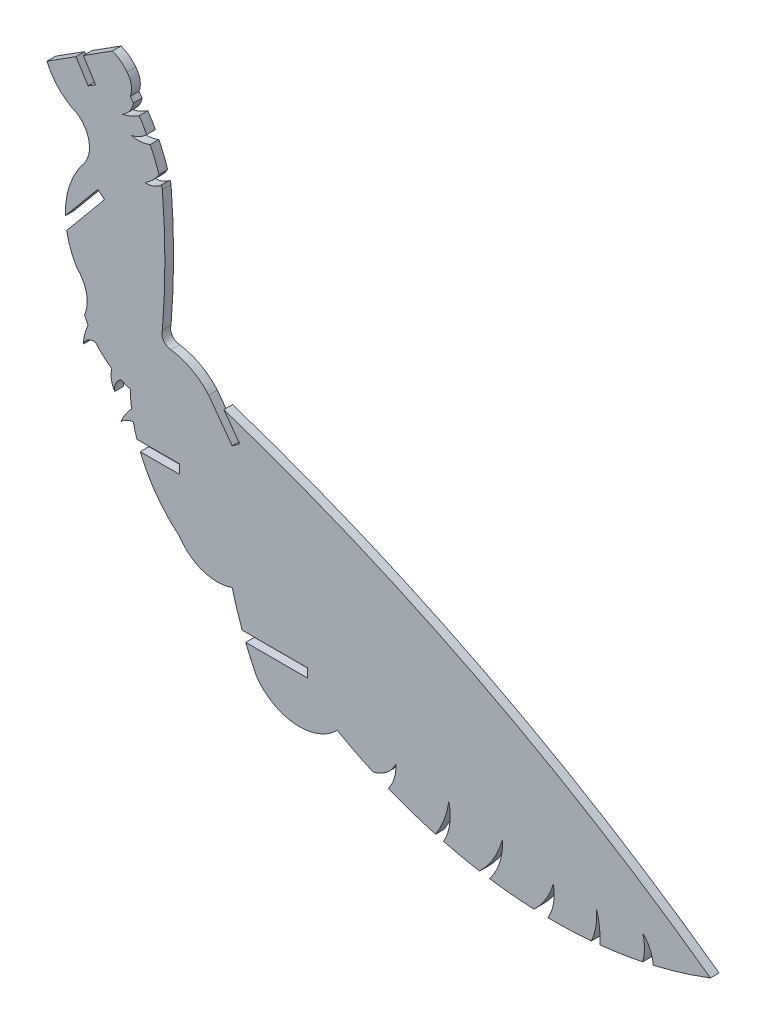
SolidWorks part; units mm, degrees
ref_plane "Front Plane" through (0, 0, 0) normal (0, 0, 1) x (1, 0, 0)
ref_plane "Top Plane" through (0, 0, 0) normal (0, 1, 0) x (1, 0, 0)
ref_plane "Right Plane" through (0, 0, 0) normal (1, 0, 0) x (0, 0, -1)
sketch "Sketch1" plane through (0, 0, 0) normal (0, 0, 1) x (1, 0, 0)
  line L0 (56.2641, 126.9569) -> (51.1749, 123.7322)
  line L1 (49.8875, 122.9166) -> (44.7982, 119.6919)
  line L2 (49.8875, 122.9166) -> (52.0204, 119.5503)
  line L3 (51.1749, 123.7322) -> (53.3078, 120.3659)
  line L4 (48.1098, 96.7709) -> (54.3007, 104.2166) construction
  line L5 (52.0204, 119.5503) -> (53.3078, 120.3659)
  line L6 (48.2561, 95.755) -> (54.8866, 103.7294)
  line L7 (48.0338, 97.8714) -> (53.7147, 104.7038)
  line L8 (48.6957, 96.2837) -> (54.8866, 103.7294) construction
  line L9 (54.8866, 103.7294) -> (53.7147, 104.7038)
  line L10 (60.5612, 70.2402) -> (68.0534, 70.2402)
  line L11 (47.5238, 97.2581) -> (53.7147, 104.7038) construction
  line L12 (68.0534, 70.2402) -> (68.0534, 68.6516)
  line L13 (68.0534, 68.6516) -> (61.1383, 68.6516)
  line L14 (78.9985, 50.5144) -> (90.4592, 50.5144)
  line L15 (90.4592, 50.5144) -> (90.4592, 48.9714)
  line L16 (90.4592, 48.9714) -> (79.6004, 48.9714)
  line L17 (73.1245, 83.2205) -> (77.2364, 77.5864)
  line L18 (77.2364, 77.5864) -> (78.5558, 78.5494)
  line L19 (78.5558, 78.5494) -> (75.7768, 82.3571)
  arc A0 (160.9536, 38.7637) -> (150.9331, 35.6905) centre (133.4657, 110.5167) cw
  arc A1 (160.9536, 38.7637) -> (75.7768, 82.3571) centre (-22.1727, -214.0359) ccw
  arc A2 (95.6239, 43.6431) -> (81.6143, 44.5745) centre (89.0225, 50.1759) cw
  arc A3 (81.6143, 44.5745) -> (79.6004, 48.9714) centre (131.8439, 70.2402) cw
  arc A4 (77.2364, 56.1066) -> (68.0534, 59.2032) centre (74.5968, 63.4434) cw
  arc A5 (68.0534, 59.2032) -> (61.1383, 68.6516) centre (83.2588, 77.5864) cw
  arc A6 (59.4044, 77.2487) -> (57.7499, 77.8796) centre (63.0644, 89.3322) cw
  arc A7 (51.3855, 84.5355) -> (50.057, 90.9475) centre (46.1797, 86.8005) ccw
  arc A8 (50.057, 90.9475) -> (48.2561, 95.755) centre (62.3927, 98.3096) cw
  arc A9 (51.3855, 107.5406) -> (50.057, 114.4006) centre (47.355, 110.3187) ccw
  arc A10 (50.057, 114.4006) -> (44.7982, 119.6919) centre (54.0592, 123.6371) cw
  arc A11 (73.1245, 83.2205) -> (66.4887, 86.8005) centre (65.0088, 76.1175) ccw
  arc A12 (66.4887, 86.8005) -> (65.0088, 89.0236) centre (66.6029, 88.4807) cw
  arc A13 (65.0088, 89.0236) -> (65.0088, 110.3187) centre (-62.101, 99.6711) ccw
  arc A14 (65.0088, 110.3187) -> (64.8446, 110.9285) centre (35.1317, 102.6017) ccw
  arc A15 (59.4044, 121.655) -> (58.8476, 125.0181) centre (56.2641, 122.8628) ccw
  arc A16 (58.8476, 125.0181) -> (56.2641, 126.9569) centre (54.3007, 121.6496) ccw
  arc A17 (48.0338, 97.8714) -> (51.3855, 107.5406) centre (62.3927, 98.3096) cw
  arc A18 (60.5612, 70.2402) -> (59.9345, 72.5741) centre (83.2588, 77.5864) cw
  arc A19 (78.9985, 50.5144) -> (77.2364, 56.1066) centre (131.8439, 70.2402) cw
  arc A20 (101.8876, 40.4675) -> (105.8798, 43.6431) centre (100.6311, 46.1442) ccw
  arc A21 (105.8798, 43.6431) -> (104.5686, 39.3196) centre (99.4447, 43.234) cw
  arc A22 (112.8373, 36.4995) -> (115.1586, 42.6215) centre (100.4265, 44.7065) ccw
  arc A23 (115.1586, 42.6215) -> (114.2389, 36.1231) centre (106.603, 40.5181) cw
  arc A24 (120.5549, 34.7712) -> (124.5727, 41.5941) centre (110.0861, 45.5303) ccw
  arc A25 (124.5727, 41.5941) -> (122.295, 34.4951) centre (113.9259, 41.0952) cw
  arc A26 (130.0552, 33.7545) -> (133.4657, 39.2835) centre (121.7304, 42.7059) ccw
  arc A27 (133.4657, 39.2835) -> (132.5118, 33.6847) centre (125.6264, 37.7385) cw
  arc A28 (140.1293, 33.9682) -> (140.9794, 39.4313) centre (130.5915, 38.2502) ccw
  arc A29 (140.9794, 39.4313) -> (141.5846, 34.1089) centre (127.8826, 35.2466) cw
  arc A30 (149.1033, 35.2868) -> (149.1033, 39.685) centre (141.5095, 37.4859) ccw
  arc A31 (149.1033, 39.685) -> (150.9331, 35.6905) centre (144.8322, 35.3121) cw
  arc A32 (149.1033, 35.2868) -> (141.5846, 34.1089) centre (133.4657, 110.5167) cw
  arc A33 (140.1293, 33.9682) -> (132.5118, 33.6847) centre (133.4657, 110.5167) cw
  arc A34 (130.0552, 33.7545) -> (122.295, 34.4951) centre (133.4657, 110.5167) cw
  arc A35 (120.5549, 34.7712) -> (114.2389, 36.1231) centre (133.4657, 110.5167) cw
  arc A36 (112.8373, 36.4995) -> (104.5686, 39.3196) centre (133.4657, 110.5167) cw
  arc A37 (101.8876, 40.4675) -> (95.6239, 43.6431) centre (133.4657, 110.5167) cw
  arc A38 (59.9345, 72.5741) -> (57.7499, 71.5041) centre (60.3625, 68.9352) ccw
  arc A39 (57.7499, 71.5041) -> (59.6212, 74.3596) centre (66.0553, 68.1023) cw
  arc A40 (57.7499, 77.8796) -> (56.6693, 75.5509) centre (58.9503, 75.9075) ccw
  arc A41 (56.6693, 75.5509) -> (56.1682, 78.7564) centre (60.0654, 77.7237) cw
  arc A42 (53.3078, 81.3189) -> (51.1749, 79.9882) centre (53.0514, 79.355) ccw
  arc A43 (51.1749, 79.9882) -> (52.0031, 83.2451) centre (59.9606, 79.4877) cw
  arc A44 (52.0031, 83.2451) -> (51.3855, 84.5355) centre (63.0644, 89.3322) cw
  arc A45 (56.1682, 78.7564) -> (53.3078, 81.3189) centre (63.0644, 89.3322) cw
  arc A46 (59.6212, 74.3596) -> (59.4044, 77.2487) centre (83.2588, 77.5864) cw
  arc A47 (59.9606, 120.9243) -> (58.0395, 118.2685) centre (56.1174, 121.6816) cw
  arc A48 (58.0395, 118.2685) -> (60.9553, 119.4935) centre (56.484, 126.054) ccw
  arc A49 (62.2727, 117.2836) -> (59.559, 115.8157) centre (58.4099, 121.1821) cw
  arc A50 (59.559, 115.8157) -> (62.8871, 116.0861) centre (60.805, 121.0963) ccw
  arc A51 (64.4294, 112.2888) -> (61.945, 109.863) centre (58.1478, 116.2369) cw
  arc A52 (61.945, 109.863) -> (64.8446, 110.9285) centre (62.1599, 113.7563) ccw
  arc A53 (64.4294, 112.2888) -> (62.8871, 116.0861) centre (35.1317, 102.6017) ccw
  arc A54 (62.2727, 117.2836) -> (60.9553, 119.4935) centre (35.1317, 102.6017) ccw
  arc A55 (59.9606, 120.9243) -> (59.4044, 121.655) centre (35.1317, 102.6017) ccw
  ellipse E0 centre (167.3354, 57.9666) end of major axis (167.3354, 94.627) minor radius 30.548 (136.8043, 56.7451) -> (148.7103, 28.9083) ccw construction
  dimension "D1" = 0.762
  dimension "D2" = 0.762
extrude "Boss-Extrude1" add sketch "Sketch1" along normal blind 1.524
